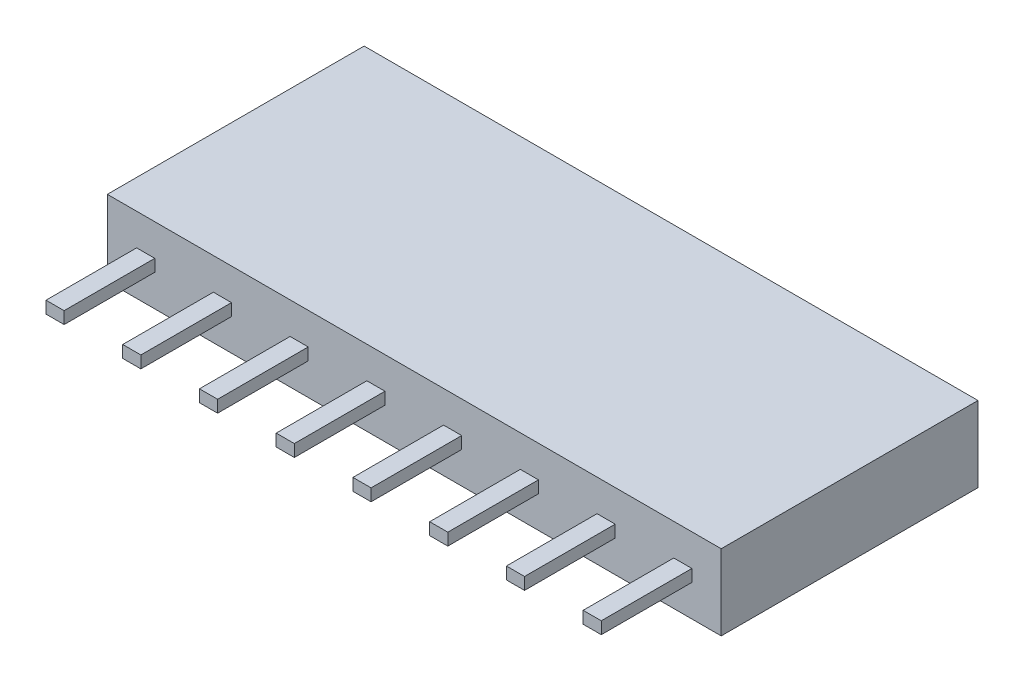
SolidWorks part; units mm, degrees
ref_plane "Front" through (0, 0, 0) normal (0, 0, 1) x (1, 0, 0)
ref_plane "Top" through (0, 0, 0) normal (0, 1, 0) x (1, 0, 0)
ref_plane "Right" through (0, 0, 0) normal (1, 0, 0) x (0, 0, -1)
sketch "Эскиз1" plane through (0, 0, 0) normal (0, 1, 0) x (1, 0, 0)
  line L1 (-10.16, 4.25) -> (10.16, 4.25)
  line L2 (-10.16, 4.25) -> (-10.16, -4.25)
  line L3 (-10.16, -4.25) -> (10.16, -4.25)
  line L4 (10.16, 4.25) -> (10.16, -4.25)
  line L5 (-10.16, 4.25) -> (10.16, -4.25) construction
  line L6 (-10.16, -4.25) -> (10.16, 4.25) construction
  point P0 (0, 0)
extrude "Бобышка-Вытянуть1" add sketch "Эскиз1" along normal blind 2.5
sketch "Эскиз2" plane through (0, 0, 4.25) normal (0, 0, 1) x (1, 0, 0)
  line L0 (-10.16, 1.25) -> (10.16, 1.25) construction
  line L1 (-10.16, 2.5) -> (-10.16, 0) construction
  line L2 (10.16, 2.5) -> (10.16, 0) construction
  line L3 (-6.65, 1.05) -> (-6.05, 1.05)
  line L4 (-9.19, 1.05) -> (-8.59, 1.05)
  line L5 (-9.19, 1.05) -> (-9.19, 1.45)
  line L6 (-9.19, 1.45) -> (-8.59, 1.45)
  line L7 (-8.59, 1.05) -> (-8.59, 1.45)
  line L8 (-9.19, 1.05) -> (-8.59, 1.45) construction
  line L9 (-9.19, 1.45) -> (-8.59, 1.05) construction
  line L10 (-6.65, 1.05) -> (-6.05, 1.45) construction
  line L11 (-6.65, 1.05) -> (-6.65, 1.45)
  line L12 (-6.65, 1.45) -> (-6.05, 1.45)
  line L13 (-6.65, 1.45) -> (-6.05, 1.05) construction
  line L14 (-6.05, 1.05) -> (-6.05, 1.45)
  line L15 (-4.11, 1.05) -> (-3.51, 1.05)
  line L16 (-4.11, 1.05) -> (-3.51, 1.45) construction
  line L17 (-4.11, 1.05) -> (-4.11, 1.45)
  line L18 (-4.11, 1.45) -> (-3.51, 1.45)
  line L19 (-4.11, 1.45) -> (-3.51, 1.05) construction
  line L20 (-3.51, 1.05) -> (-3.51, 1.45)
  line L21 (-1.57, 1.05) -> (-0.97, 1.05)
  line L22 (-1.57, 1.05) -> (-0.97, 1.45) construction
  line L23 (-1.57, 1.05) -> (-1.57, 1.45)
  line L24 (-1.57, 1.45) -> (-0.97, 1.45)
  line L25 (-1.57, 1.45) -> (-0.97, 1.05) construction
  line L26 (-0.97, 1.05) -> (-0.97, 1.45)
  line L27 (0.97, 1.05) -> (1.57, 1.05)
  line L28 (0.97, 1.05) -> (1.57, 1.45) construction
  line L29 (0.97, 1.05) -> (0.97, 1.45)
  line L30 (0.97, 1.45) -> (1.57, 1.45)
  line L31 (0.97, 1.45) -> (1.57, 1.05) construction
  line L32 (1.57, 1.05) -> (1.57, 1.45)
  line L33 (3.51, 1.05) -> (4.11, 1.05)
  line L34 (3.51, 1.05) -> (4.11, 1.45) construction
  line L35 (3.51, 1.05) -> (3.51, 1.45)
  line L36 (3.51, 1.45) -> (4.11, 1.45)
  line L37 (3.51, 1.45) -> (4.11, 1.05) construction
  line L38 (4.11, 1.05) -> (4.11, 1.45)
  line L39 (6.05, 1.05) -> (6.65, 1.05)
  line L40 (6.05, 1.05) -> (6.65, 1.45) construction
  line L41 (6.05, 1.05) -> (6.05, 1.45)
  line L42 (6.05, 1.45) -> (6.65, 1.45)
  line L43 (6.05, 1.45) -> (6.65, 1.05) construction
  line L44 (6.65, 1.05) -> (6.65, 1.45)
  line L45 (8.59, 1.05) -> (9.19, 1.05)
  line L46 (8.59, 1.05) -> (9.19, 1.45) construction
  line L47 (8.59, 1.05) -> (8.59, 1.45)
  line L48 (8.59, 1.45) -> (9.19, 1.45)
  line L49 (8.59, 1.45) -> (9.19, 1.05) construction
  line L50 (9.19, 1.05) -> (9.19, 1.45)
  dimension "D1" = 8
extrude "Бобышка-Вытянуть2" add sketch "Эскиз2" along normal blind 3
